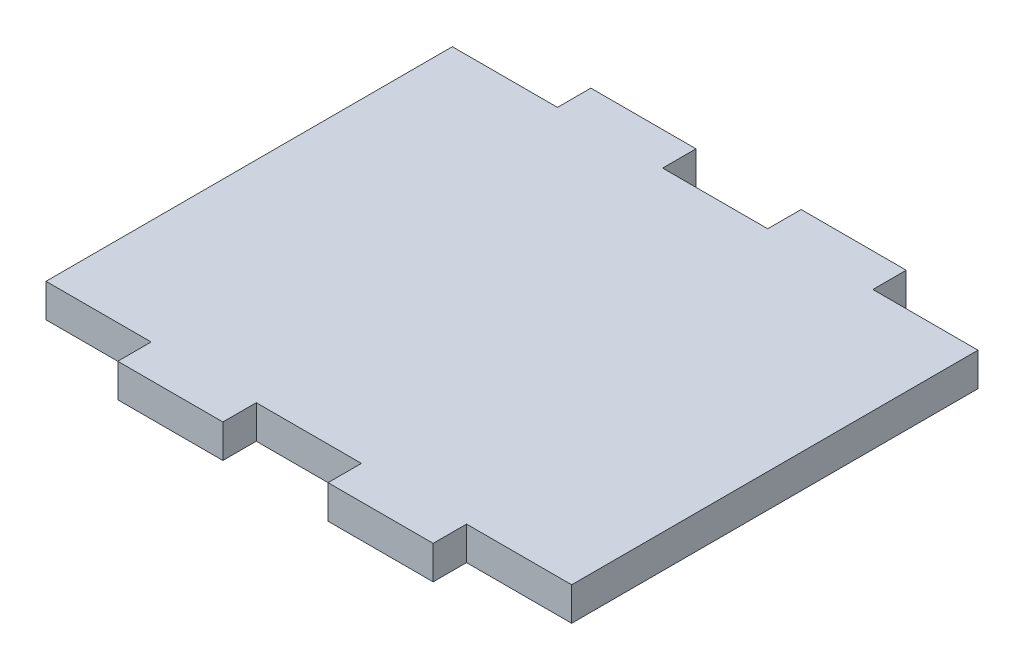
SolidWorks part; units mm, degrees
material "Mahogany"
ref_plane "Front Plane" through (0, 0, 0) normal (0, 0, 1) x (1, 0, 0)
ref_plane "Top Plane" through (0, 0, 0) normal (0, 1, 0) x (1, 0, 0)
ref_plane "Right Plane" through (0, 0, 0) normal (1, 0, 0) x (0, 0, -1)
sketch "Sketch1" plane through (0, 0, 0) normal (0, 1, 0) x (1, 0, 0)
  line L0 (0, 22.5) -> (50000, 22.5) construction
  line L1 (0, 0) -> (70, 0) construction
  line L2 (0, 3.175) -> (0, 41.825)
  line L3 (0, 45) -> (50, 45) construction
  line L4 (50, 3.175) -> (50, 41.825)
  line L5 (10, 45) -> (20, 45)
  line L6 (10, 45) -> (10, 41.825)
  line L7 (10, 41.825) -> (20, 41.825) construction
  line L8 (20, 45) -> (20, 41.825)
  line L9 (20, 0) -> (20, 3.175)
  line L10 (10, 3.175) -> (20, 3.175) construction
  line L11 (10, 0) -> (10, 3.175)
  line L12 (30, 45) -> (30, 41.825)
  line L13 (30, 41.825) -> (40, 41.825) construction
  line L14 (40, 45) -> (40, 41.825)
  line L15 (30, 3.175) -> (40, 3.175) construction
  line L16 (40, 0) -> (40, 3.175)
  line L17 (30, 0) -> (30, 3.175)
  line L19 (20, 45) -> (30, 45) construction
  line L21 (0, 0) -> (10, 0) construction
  line L22 (20, 0) -> (30, 0) construction
  line L23 (40, 0) -> (70, 0) construction
  line L24 (0, 41.825) -> (10, 41.825)
  line L25 (20, 41.825) -> (30, 41.825)
  line L26 (40, 41.825) -> (50, 41.825)
  line L27 (10, 3.175) -> (0, 3.175)
  line L28 (20, 3.175) -> (30, 3.175)
  line L29 (40, 3.175) -> (50, 3.175)
  line L30 (10, 0) -> (20, 0)
  line L31 (30, 0) -> (40, 0)
  line L32 (30, 45) -> (40, 45)
  point P18 (10, 43.4125)
  dimension "D1" = 45
  dimension "D4" = 10
  dimension "D5" = 10
  dimension "D6" = 10
  dimension "D7" = 3.175
  dimension "D2" = 50
  dimension "D3" = 2
extrude "Boss-Extrude1" add sketch "Sketch1" along normal blind 3.175
equation "\"T\"= 0.125in'Material Thickness"
equation "\"L_f\"= 20mm'Length of front platform"
equation "\"L_m\"= 70mm'Lenght of mid platform"
equation "\"L_b\"= 20mm'Length of back platform"
equation "\"L_f_t\"= 5mm'Length of front indent on top"
equation "\"L_b_t\"= 15mm'Length of back indent on top"
equation "\"L_m_t\"= \"L_m\" - \"L_b_t\" - \"L_f_t\"'Length of top platform"
equation "\"W\"= 45mm'Width of basket"
equation "\"H\"= 30mm'Height of basket"
equation "\"W_min\"= round ( 1.25 * \"T\" )'Minimum width of parts"
equation "\"D1@Sketch1\"=\"W\""
equation "\"D4@Sketch1\"=\"L_m_t\"/5"
equation "\"D5@Sketch1\"=\"L_m_t\"/5"
equation "\"D6@Sketch1\"=\"L_m_t\"/5"
equation "\"D7@Sketch1\"=\"T\""
equation "\"D1@Boss-Extrude1\"=\"T\""
equation "\"D2@Sketch1\"=\"L_m_t\""
